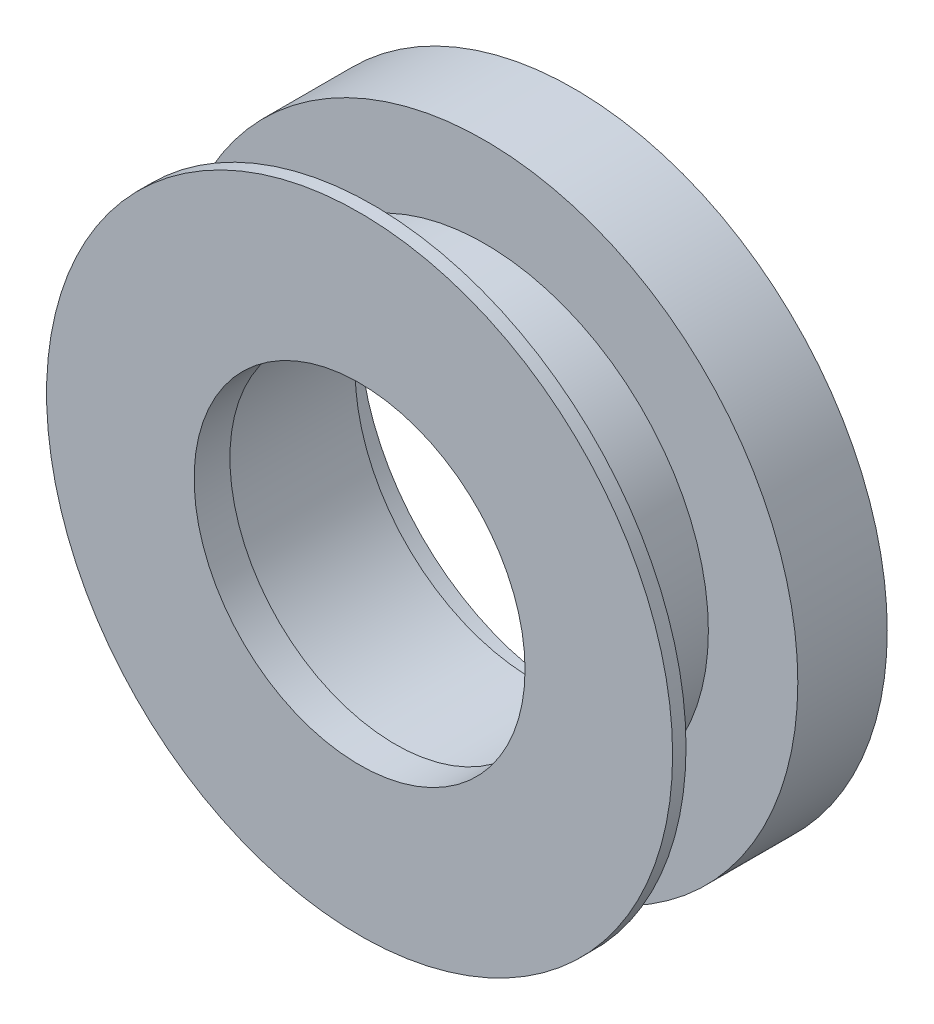
SolidWorks part; units mm, degrees
material "7075-T6 (SN)"
ref_plane "Front Plane" through (0, 0, 0) normal (0, 0, 1) x (1, 0, 0)
ref_plane "Top Plane" through (0, 0, 0) normal (0, 1, 0) x (1, 0, 0)
ref_plane "Right Plane" through (0, 0, 0) normal (1, 0, 0) x (0, 0, -1)
sketch "Sketch1" plane through (0, 0, 0) normal (0, 0, 1) x (1, 0, 0)
  circle A0 centre (0, 0) radius 5
  circle A1 centre (0, 0) radius 4
extrude "D10_Pilot_And_M10x0p5_Thread_Envelope" add sketch "Sketch1" along normal blind 2 from offset 1
sketch "Sketch2" plane through (0, 0, 0) normal (0, 0, 1) x (1, 0, 0)
  circle A0 centre (0, 0) radius 5
  circle A1 centre (0, 0) radius 3.7
extrude "Outer_Race_Inner_Shoulder_ID7p4" add sketch "Sketch2" along normal blind 0.8 from offset 1
sketch "Sketch3" plane through (0, 0, 0) normal (0, 0, 1) x (1, 0, 0)
  circle A0 centre (0, 0) radius 7
  circle A1 centre (0, 0) radius 3.7
extrude "Inboard_G10_Retention_Flange_H0p3" add sketch "Sketch3" along normal blind 0.3 from offset 1.5
sketch "Sketch4" plane through (0, 0, 0) normal (0, 0, 1) x (1, 0, 0)
  circle A0 centre (0, 0) radius 7
  circle A1 centre (0, 0) radius 4
extrude "M14x0p5_Bearing_Cap_Boss" add sketch "Sketch4" along normal blind 1.1 from offset 2.1
sketch "Sketch5" plane through (0, 0, 0) normal (0, 0, 1) x (1, 0, 0)
  circle A0 centre (0, 0) radius 7
  circle A1 centre (0, 0) radius 4.8
extrude "Flanged_Race_Pocket_D9p6" add sketch "Sketch5" along normal blind 0.9 from offset 3
